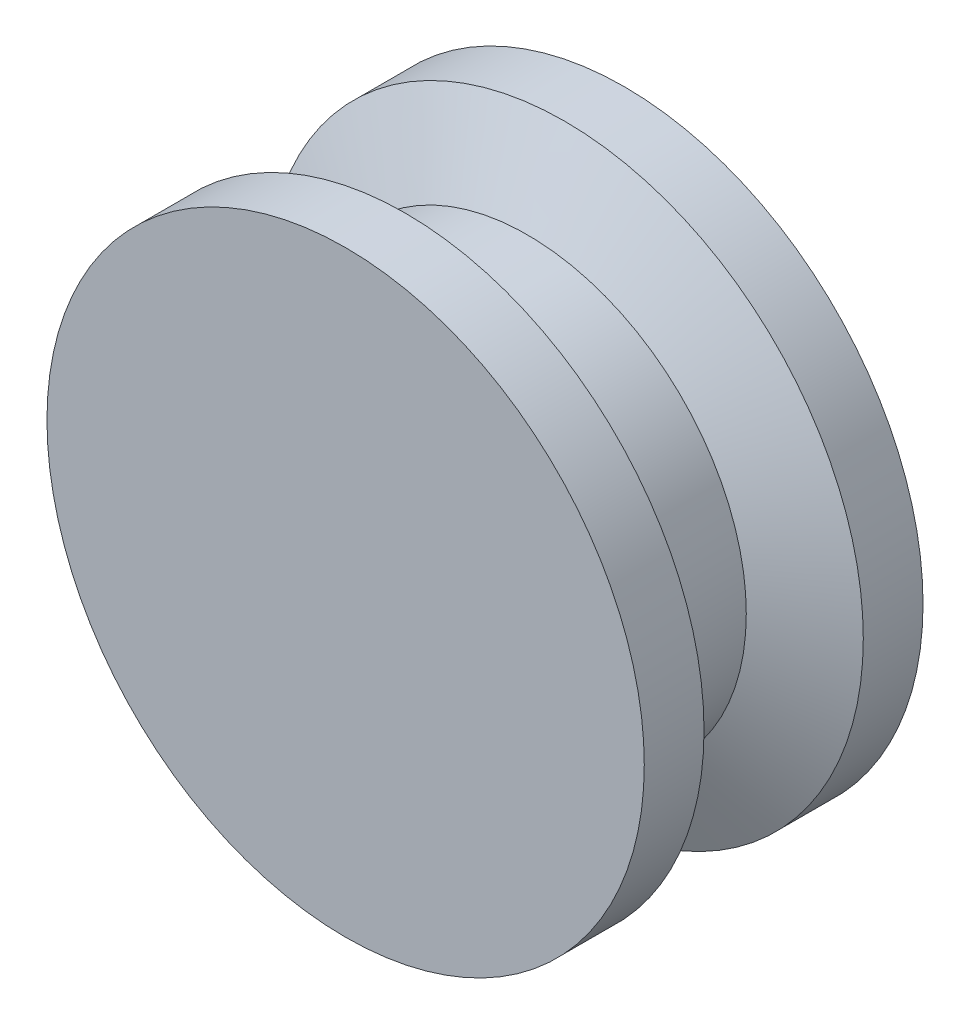
SolidWorks part; units mm, degrees
ref_plane "Front Plane" through (0, 0, 0) normal (0, 0, 1) x (1, 0, 0)
ref_plane "Top Plane" through (0, 0, 0) normal (0, 1, 0) x (1, 0, 0)
ref_plane "Right Plane" through (0, 0, 0) normal (1, 0, 0) x (0, 0, -1)
sketch "Sketch1" plane through (0, 0, 0) normal (0, 1, 0) x (1, 0, 0)
  line L1 (-199.2343, 0) -> (232.0832, 0) construction
  line L2 (0, 70) -> (150, 70)
  line L3 (150, 70) -> (150, 40)
  line L4 (150, 40) -> (109.9201, 21.3104)
  line L5 (109.9201, 21.3104) -> (109.9201, -21.3104)
  line L6 (150, -40) -> (109.9201, -21.3104)
  line L7 (150, -70) -> (150, -40)
  line L8 (0, -70) -> (150, -70)
  line L9 (0, 161.8308) -> (0, -229.0471) construction
  line L10 (0, 70) -> (0, -70)
  point P6 (0, 0)
  point P7 (0, 0)
  point P12 (109.9201, 0)
  dimension "D1" = 70
  dimension "D2" = 115
revolve "Revolve2" add sketch "Sketch1" angle 360 about L9
